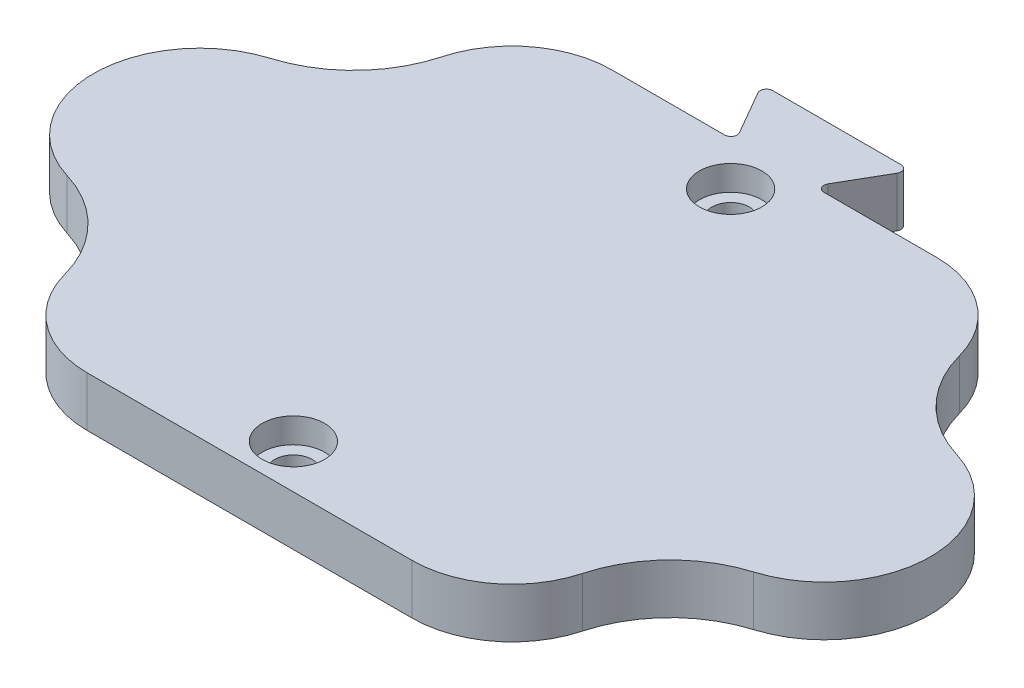
SolidWorks part; units mm, degrees
ref_plane "Спереди" through (0, 0, 0) normal (0, 0, 1) x (1, 0, 0)
ref_plane "Сверху" through (0, 0, 0) normal (0, 1, 0) x (1, 0, 0)
ref_plane "Справа" through (0, 0, 0) normal (1, 0, 0) x (0, 0, -1)
sketch "Эскиз1" plane through (0, 0, 0) normal (0, 1, 0) x (1, 0, 0)
  line L1 (-50, -50) -> (50, -50)
  line L2 (-50, -50) -> (-50, 50)
  line L3 (-50, 50) -> (50, 50)
  line L4 (50, -50) -> (50, 50)
  line L5 (-50, -50) -> (50, 50) construction
  line L6 (-50, 50) -> (50, -50) construction
  point P0 (0, 0)
  dimension "D1" = 100
extrude "Бобышка-Вытянуть1" add sketch "Эскиз1" along normal blind 4
sketch "Эскиз4" plane through (0, 4, 0) normal (0, 1, 0) x (1, 0, 0)
  line L4 (50, -50) -> (50, 50)
  line L5 (50, 50) -> (-50, 50)
  line L6 (-50, 50) -> (-50, -50)
  line L7 (-50, -50) -> (50, -50)
  line L8 (50, -50) -> (50, 50)
  line L9 (50, 50) -> (-50, 50)
  line L10 (-50, 50) -> (-50, -50)
  line L11 (-50, -50) -> (50, -50)
  line L14 (3.5463, 21.75) -> (5.567, 25.25)
  line L15 (5.134, 26) -> (-5.134, 26)
  line L16 (-5.567, 25.25) -> (-3.5463, 21.75)
  line L17 (-3.9793, 21) -> (-13, 21)
  line L18 (-13, -21) -> (13, -21)
  line L19 (13, 21) -> (3.9793, 21)
  line L20 (3.5463, 21.75) -> (5.567, 25.25)
  line L21 (5.134, 26) -> (-5.134, 26)
  line L22 (-5.567, 25.25) -> (-3.5463, 21.75)
  line L23 (-3.9793, 21) -> (-13, 21)
  line L24 (-13, -21) -> (13, -21)
  line L25 (13, 21) -> (3.9793, 21)
  arc A14 (5.567, 25.25) -> (5.134, 26) centre (5.134, 25.5) ccw
  arc A15 (-5.134, 26) -> (-5.567, 25.25) centre (-5.134, 25.5) ccw
  arc A16 (-3.9793, 21) -> (-3.5463, 21.75) centre (-3.9793, 21.5) ccw
  arc A17 (-13, 21) -> (-20.7222, 15.0898) centre (-13, 13) ccw
  arc A18 (-27.4696, 8.1333) -> (-20.7222, 15.0898) centre (-30.375, 17.702) ccw
  arc A19 (-27.4696, 8.1333) -> (-27.4696, -8.1333) centre (-25, 0) ccw
  arc A20 (-20.7222, -15.0898) -> (-27.4696, -8.1333) centre (-30.375, -17.702) ccw
  arc A21 (-20.7222, -15.0898) -> (-13, -21) centre (-13, -13) ccw
  arc A22 (13, -21) -> (20.7222, -15.0898) centre (13, -13) ccw
  arc A23 (27.4696, -8.1333) -> (20.7222, -15.0898) centre (30.375, -17.702) ccw
  arc A24 (27.4696, -8.1333) -> (27.4696, 8.1333) centre (25, 0) ccw
  arc A25 (20.7222, 15.0898) -> (27.4696, 8.1333) centre (30.375, 17.702) ccw
  arc A26 (20.7222, 15.0898) -> (13, 21) centre (13, 13) ccw
  arc A27 (3.5463, 21.75) -> (3.9793, 21) centre (3.9793, 21.5) ccw
  arc A28 (5.567, 25.25) -> (5.134, 26) centre (5.134, 25.5) ccw
  arc A29 (-5.134, 26) -> (-5.567, 25.25) centre (-5.134, 25.5) ccw
  arc A30 (-3.9793, 21) -> (-3.5463, 21.75) centre (-3.9793, 21.5) ccw
  arc A31 (-13, 21) -> (-20.7222, 15.0898) centre (-13, 13) ccw
  arc A32 (-27.4696, 8.1333) -> (-20.7222, 15.0898) centre (-30.375, 17.702) ccw
  arc A33 (-27.4696, 8.1333) -> (-27.4696, -8.1333) centre (-25, 0) ccw
  arc A34 (-20.7222, -15.0898) -> (-27.4696, -8.1333) centre (-30.375, -17.702) ccw
  arc A35 (-20.7222, -15.0898) -> (-13, -21) centre (-13, -13) ccw
  arc A36 (13, -21) -> (20.7222, -15.0898) centre (13, -13) ccw
  arc A37 (27.4696, -8.1333) -> (20.7222, -15.0898) centre (30.375, -17.702) ccw
  arc A38 (27.4696, -8.1333) -> (27.4696, 8.1333) centre (25, 0) ccw
  arc A39 (20.7222, 15.0898) -> (27.4696, 8.1333) centre (30.375, 17.702) ccw
  arc A40 (20.7222, 15.0898) -> (13, 21) centre (13, 13) ccw
  arc A41 (3.5463, 21.75) -> (3.9793, 21) centre (3.9793, 21.5) ccw
  line M25 (50, -50) -> (50, 50)
  line M26 (50, 50) -> (-50, 50)
  line M27 (-50, 50) -> (-50, -50)
  line M28 (-50, -50) -> (50, -50)
  dimension "D1" = 0
  dimension "D2" = 0
extrude "Вырез-Вытянуть1" cut sketch "Эскиз4" against normal through all contours L20 A41 L25 A40 A39 A38 A37 A36 L24 A35 A34 A33 A32 A31 L23 A30 L22 A29 L21 A28 M28 M25 M26 M27 | L8 L9 L10 L11
sketch "Эскиз5" plane through (0, 0, 0) normal (0, -1, 0) x (1, 0, 0)
  line L0 (14.6235, 0.9705) -> (14.6235, -0.9705) construction
  line L1 (0.9705, -14.6235) -> (-0.9705, -14.6235) construction
  line L2 (-14.6235, -0.9705) -> (-14.6235, 0.9705) construction
  line L3 (-0.9705, 14.6235) -> (0.9705, 14.6235) construction
  line L4 (14.6235, 0.9705) -> (14.6235, -0.9705)
  line L5 (0.9705, -14.6235) -> (-0.9705, -14.6235)
  line L6 (-14.6235, -0.9705) -> (-14.6235, 0.9705)
  line L7 (-0.9705, 14.6235) -> (0.9705, 14.6235)
  line L8 (-0.9705, 14.0235) -> (0.9705, 14.0235)
  line L9 (-14.0235, -0.9705) -> (-14.0235, 0.9705)
  line L10 (0.9705, -14.0235) -> (-0.9705, -14.0235)
  line L11 (14.0235, 0.9705) -> (14.0235, -0.9705)
  circle A0 centre (-25, 0) radius 6.5 construction
  circle A1 centre (25, 0) radius 6.5 construction
  arc A22 (14.6235, -0.9705) -> (15.0403, -1.7828) centre (15.6235, -0.9705) ccw construction
  arc A25 (15.0403, 1.7828) -> (14.6235, 0.9705) centre (15.6235, 0.9705) ccw construction
  arc A85 (-0.9705, -14.6235) -> (-1.7828, -15.0403) centre (-0.9705, -15.6235) ccw construction
  arc A86 (1.7828, -15.0403) -> (15.0403, -1.7828) centre (9.5, -9.5) ccw construction
  arc A87 (1.7828, -15.0403) -> (0.9705, -14.6235) centre (0.9705, -15.6235) ccw construction
  arc A88 (-15.0403, -1.7828) -> (-1.7828, -15.0403) centre (-9.5, -9.5) ccw construction
  arc A89 (-15.0403, -1.7828) -> (-14.6235, -0.9705) centre (-15.6235, -0.9705) ccw construction
  arc A90 (-14.6235, 0.9705) -> (-15.0403, 1.7828) centre (-15.6235, 0.9705) ccw construction
  arc A91 (-1.7828, 15.0403) -> (-15.0403, 1.7828) centre (-9.5, 9.5) ccw construction
  arc A92 (-1.7828, 15.0403) -> (-0.9705, 14.6235) centre (-0.9705, 15.6235) ccw construction
  arc A93 (0.9705, 14.6235) -> (1.7828, 15.0403) centre (0.9705, 15.6235) ccw construction
  arc A94 (15.0403, 1.7828) -> (1.7828, 15.0403) centre (9.5, 9.5) ccw construction
  circle A95 centre (-25, 0) radius 6.5
  circle A112 centre (25, 0) radius 6.5
  arc A113 (14.6235, -0.9705) -> (15.0403, -1.7828) centre (15.6235, -0.9705) ccw
  arc A114 (15.0403, 1.7828) -> (14.6235, 0.9705) centre (15.6235, 0.9705) ccw
  arc A115 (-0.9705, -14.6235) -> (-1.7828, -15.0403) centre (-0.9705, -15.6235) ccw
  arc A116 (1.7828, -15.0403) -> (15.0403, -1.7828) centre (9.5, -9.5) ccw
  arc A117 (1.7828, -15.0403) -> (0.9705, -14.6235) centre (0.9705, -15.6235) ccw
  arc A118 (-15.0403, -1.7828) -> (-1.7828, -15.0403) centre (-9.5, -9.5) ccw
  arc A119 (-15.0403, -1.7828) -> (-14.6235, -0.9705) centre (-15.6235, -0.9705) ccw
  arc A120 (-14.6235, 0.9705) -> (-15.0403, 1.7828) centre (-15.6235, 0.9705) ccw
  arc A121 (-1.7828, 15.0403) -> (-15.0403, 1.7828) centre (-9.5, 9.5) ccw
  arc A122 (-1.7828, 15.0403) -> (-0.9705, 14.6235) centre (-0.9705, 15.6235) ccw
  arc A123 (0.9705, 14.6235) -> (1.7828, 15.0403) centre (0.9705, 15.6235) ccw
  arc A124 (15.0403, 1.7828) -> (1.7828, 15.0403) centre (9.5, 9.5) ccw
  arc A125 (14.6904, 2.2702) -> (2.2702, 14.6904) centre (9.5, 9.5) ccw
  arc A126 (0.9705, 14.0235) -> (2.2702, 14.6904) centre (0.9705, 15.6235) ccw
  arc A127 (-2.2702, 14.6904) -> (-0.9705, 14.0235) centre (-0.9705, 15.6235) ccw
  arc A128 (-2.2702, 14.6904) -> (-14.6904, 2.2702) centre (-9.5, 9.5) ccw
  arc A129 (-14.0235, 0.9705) -> (-14.6904, 2.2702) centre (-15.6235, 0.9705) ccw
  arc A130 (-14.6904, -2.2702) -> (-14.0235, -0.9705) centre (-15.6235, -0.9705) ccw
  arc A131 (-14.6904, -2.2702) -> (-2.2702, -14.6904) centre (-9.5, -9.5) ccw
  arc A132 (-0.9705, -14.0235) -> (-2.2702, -14.6904) centre (-0.9705, -15.6235) ccw
  arc A133 (2.2702, -14.6904) -> (0.9705, -14.0235) centre (0.9705, -15.6235) ccw
  arc A134 (2.2702, -14.6904) -> (14.6904, -2.2702) centre (9.5, -9.5) ccw
  arc A135 (14.0235, -0.9705) -> (14.6904, -2.2702) centre (15.6235, -0.9705) ccw
  arc A136 (14.6904, 2.2702) -> (14.0235, 0.9705) centre (15.6235, 0.9705) ccw
  circle A137 centre (25, 0) radius 5.9
  circle A138 centre (-25, 0) radius 5.9
  dimension "D1" = 0.6
extrude "Бобышка-Вытянуть2" add sketch "Эскиз5" along normal blind 1
sketch "Эскиз6" plane through (0, 4, 0) normal (0, 1, 0) x (1, 0, 0)
  line L6 (3.5463, 21.75) -> (5.567, 25.25)
  line L7 (5.134, 26) -> (-5.134, 26)
  line L8 (-5.567, 25.25) -> (-3.5463, 21.75)
  line L9 (-3.9793, 21) -> (-13, 21)
  line L10 (-13, -21) -> (13, -21)
  line L11 (13, 21) -> (3.9793, 21)
  line L12 (3.5463, 21.75) -> (5.567, 25.25)
  line L13 (5.134, 26) -> (-5.134, 26)
  line L14 (-5.567, 25.25) -> (-3.5463, 21.75)
  line L15 (-3.9793, 21) -> (-13, 21)
  line L16 (-13, -21) -> (13, -21)
  line L17 (13, 21) -> (3.9793, 21)
  circle A0 centre (0, 17.5) radius 1 construction
  circle A1 centre (0, -17.5) radius 1 construction
  circle A2 centre (0, 17.5) radius 1
  circle A3 centre (0, -17.5) radius 1
  circle A4 centre (0, 17.5) radius 1.5
  circle A5 centre (0, -17.5) radius 1.5
  arc A14 (5.567, 25.25) -> (5.134, 26) centre (5.134, 25.5) ccw
  arc A15 (-5.134, 26) -> (-5.567, 25.25) centre (-5.134, 25.5) ccw
  arc A16 (-3.9793, 21) -> (-3.5463, 21.75) centre (-3.9793, 21.5) ccw
  arc A17 (-13, 21) -> (-20.7222, 15.0898) centre (-13, 13) ccw
  arc A18 (-27.4696, 8.1333) -> (-20.7222, 15.0898) centre (-30.375, 17.702) ccw
  arc A19 (-27.4696, 8.1333) -> (-27.4696, -8.1333) centre (-25, 0) ccw
  arc A20 (-20.7222, -15.0898) -> (-27.4696, -8.1333) centre (-30.375, -17.702) ccw
  arc A21 (-20.7222, -15.0898) -> (-13, -21) centre (-13, -13) ccw
  arc A22 (13, -21) -> (20.7222, -15.0898) centre (13, -13) ccw
  arc A23 (27.4696, -8.1333) -> (20.7222, -15.0898) centre (30.375, -17.702) ccw
  arc A24 (27.4696, -8.1333) -> (27.4696, 8.1333) centre (25, 0) ccw
  arc A25 (20.7222, 15.0898) -> (27.4696, 8.1333) centre (30.375, 17.702) ccw
  arc A26 (20.7222, 15.0898) -> (13, 21) centre (13, 13) ccw
  arc A27 (3.5463, 21.75) -> (3.9793, 21) centre (3.9793, 21.5) ccw
  arc A28 (5.567, 25.25) -> (5.134, 26) centre (5.134, 25.5) ccw
  arc A29 (-5.134, 26) -> (-5.567, 25.25) centre (-5.134, 25.5) ccw
  arc A30 (-3.9793, 21) -> (-3.5463, 21.75) centre (-3.9793, 21.5) ccw
  arc A31 (-13, 21) -> (-20.7222, 15.0898) centre (-13, 13) ccw
  arc A32 (-27.4696, 8.1333) -> (-20.7222, 15.0898) centre (-30.375, 17.702) ccw
  arc A33 (-27.4696, 8.1333) -> (-27.4696, -8.1333) centre (-25, 0) ccw
  arc A34 (-20.7222, -15.0898) -> (-27.4696, -8.1333) centre (-30.375, -17.702) ccw
  arc A35 (-20.7222, -15.0898) -> (-13, -21) centre (-13, -13) ccw
  arc A36 (13, -21) -> (20.7222, -15.0898) centre (13, -13) ccw
  arc A37 (27.4696, -8.1333) -> (20.7222, -15.0898) centre (30.375, -17.702) ccw
  arc A38 (27.4696, -8.1333) -> (27.4696, 8.1333) centre (25, 0) ccw
  arc A39 (20.7222, 15.0898) -> (27.4696, 8.1333) centre (30.375, 17.702) ccw
  arc A40 (20.7222, 15.0898) -> (13, 21) centre (13, 13) ccw
  arc A41 (3.5463, 21.75) -> (3.9793, 21) centre (3.9793, 21.5) ccw
  dimension "D2" = 3
  dimension "D1" = 0
extrude "Вырез-Вытянуть2" cut sketch "Эскиз6" against normal through all contours A4 A2 | A2 | A3 | A5 A3
sketch "Эскиз7" plane through (0, 4, 0) normal (0, 1, 0) x (1, 0, 0)
  circle A0 centre (0, 17.5) radius 2.5
  circle A1 centre (0, -17.5) radius 2.5
  dimension "D1" = 5
extrude "Вырез-Вытянуть3" cut sketch "Эскиз7" against normal blind 2
